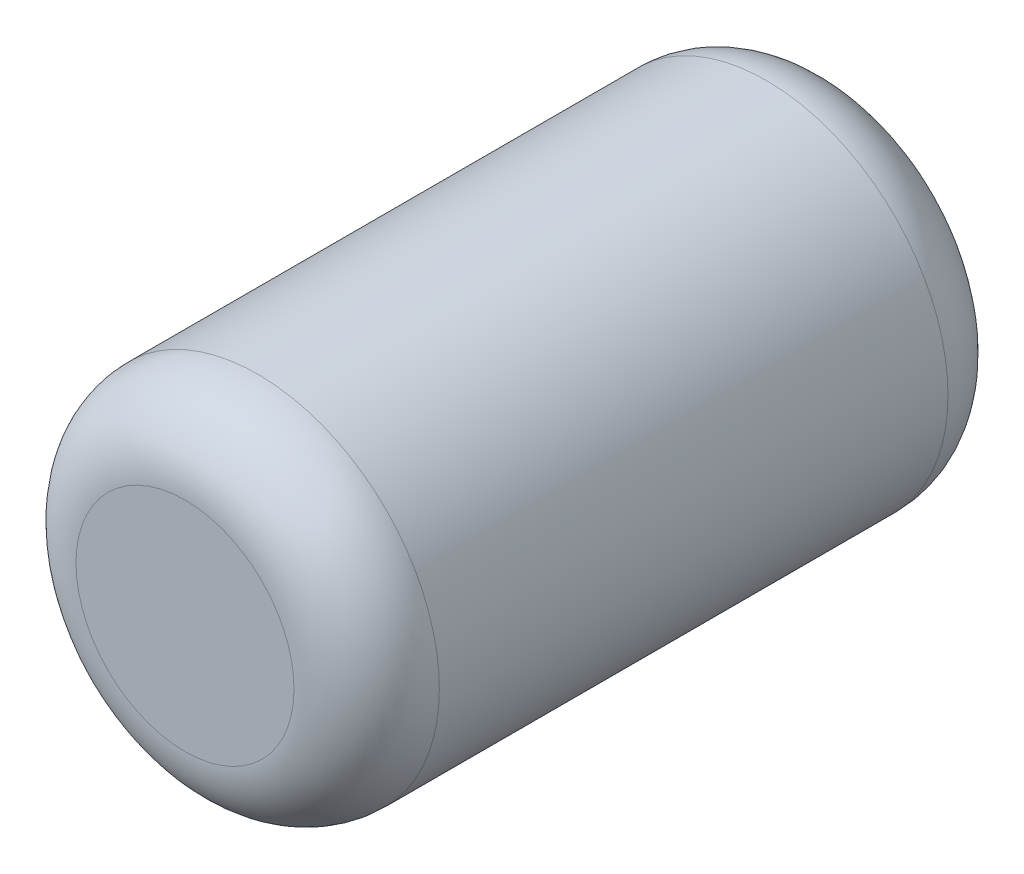
SolidWorks part; units mm, degrees
ref_plane "Front Plane" through (0, 0, 0) normal (0, 0, 1) x (1, 0, 0)
ref_plane "Top Plane" through (0, 0, 0) normal (0, 1, 0) x (1, 0, 0)
ref_plane "Right Plane" through (0, 0, 0) normal (1, 0, 0) x (0, 0, -1)
sketch "Sketch1" plane through (0, 0, 0) normal (0, 0, 1) x (1, 0, 0)
  circle A0 centre (0, 0) radius 63.5
  dimension "D1" = 127
extrude "Boss-Extrude1" add sketch "Sketch1" along normal blind 228.6
sketch "Sketch2" plane through (0, 0, 0) normal (0, 1, 0) x (1, 0, 0)
  line L0 (0, 62.7487) -> (0, -336.0396) construction
  line L1 (-63.5, -228.6) -> (63.5, -228.6) construction
  point P3 (0, 0)
  point P4 (0, -228.6)
fillet "Fillet1" radius 25.4 2 edges at (63.5, 0, 228.6) (63.5, 0, 0)
